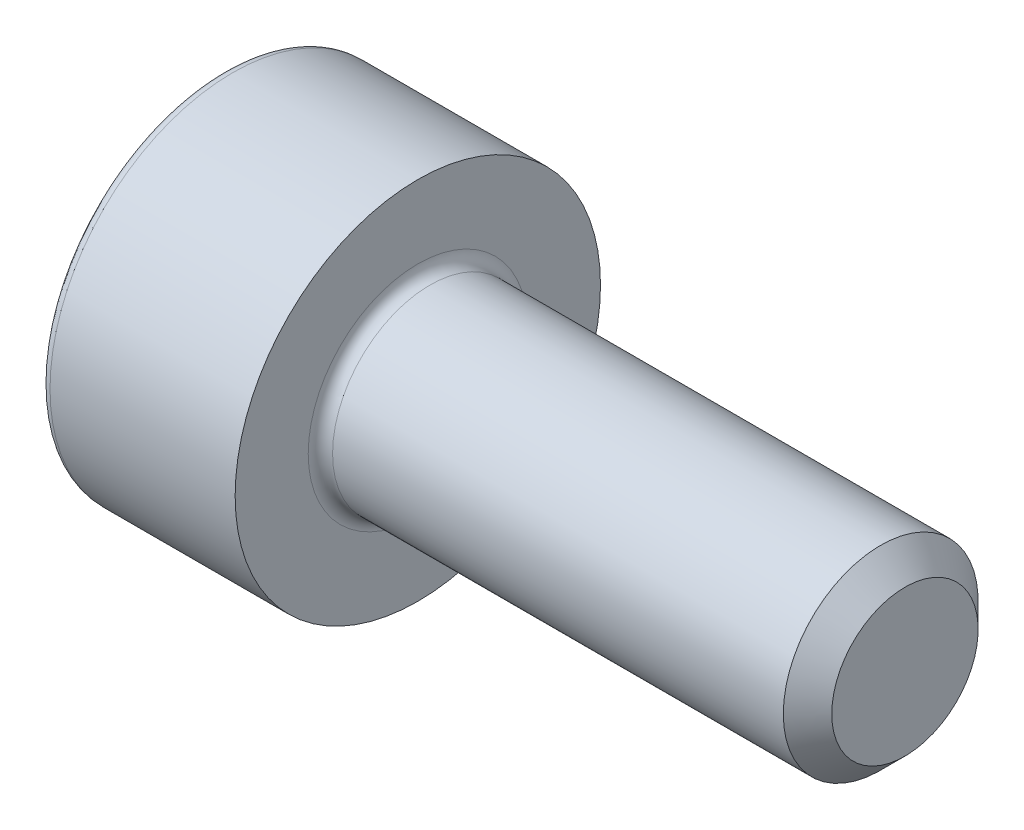
SolidWorks part; units mm, degrees
ref_plane "Front Plane" through (0, 0, 0) normal (0, 0, 1) x (1, 0, 0)
ref_plane "Top Plane" through (0, 0, 0) normal (0, 1, 0) x (1, 0, 0)
ref_plane "Right Plane" through (0, 0, 0) normal (1, 0, 0) x (0, 0, -1)
other "Configuration Table"
sketch "BodySke" plane through (0, 0, 0) normal (0, 0, 1) x (1, 0, 0)
  line L0 (0, 0) -> (5.8492, 0) construction
  line L1 (0, 0) -> (0, 1.5)
  line L2 (0, 1.5) -> (1.6, 1.5)
  line L3 (1.6, 1.5) -> (1.6, 0.8)
  line L4 (1.6, 0.8) -> (5.401, 0.8)
  line L5 (5.401, 0.8) -> (5.6, 0.601)
  line L6 (5.6, 0.601) -> (5.6, 0)
  line L7 (5.6, 0) -> (0, 0)
  line L8 (1.6, 0) -> (1.6, 0.601) construction
  line L9 (1.95, 1.5877) -> (1.95, 0.9267) construction
  dimension "Thread_length" = 4
  dimension "Diameter" = 1.6
  dimension "Thread_minor" = 1.202
  dimension "Body_chamfer_angle" = 45
  dimension "Length" = 4
  dimension "Head_diameter" = 3
  dimension "Head_length" = 1.6
  dimension "Advance" = 0.35
revolve "BaseBody" add sketch "BodySke" angle 360 about L0
cosmetic thread "ThreadCosmetic" [suppressed] parameters "Thread_length"=4, "Thread_minor"=1.202
fillet "Fillet1" radius 0.1 1 edges at (1.6, 0, 0.8)
fillet "Fillet2" radius 0.08 1 edges at (0, 0, 1.5)
sketch "HexSke" plane through (0, 0, 0) normal (1, 0, 0) x (0, 0, -1)
  line L1 (0, 0.866) -> (-0.75, 0.433)
  line L2 (-0.75, 0.433) -> (-0.75, -0.433)
  line L3 (-0.75, -0.433) -> (0, -0.866)
  line L4 (0, -0.866) -> (0.75, -0.433)
  line L5 (0.75, -0.433) -> (0.75, 0.433)
  line L6 (0.75, 0.433) -> (0, 0.866)
  circle A0 centre (0, 0) radius 0.75 construction
  dimension "Hex_size" = 1.5
extrude "Hex" cut sketch "HexSke" along normal blind 0.7
sketch "Hex-PreBroachSke" plane through (0, 0, 0) normal (0, 0, 1) x (1, 0, 0)
  line L0 (0, 0) -> (4.7325, 0) construction
  line L1 (0, 1.42) -> (0, -1.42) construction
  line L2 (0, 0) -> (0, 0.75)
  line L3 (0, 0.75) -> (0.7, 0.75)
  line L4 (0.7, 0.75) -> (1.133, 0)
  line L5 (1.133, 0) -> (0, 0)
  dimension "Hex_depth" = 0.7
  dimension "D1" = 1.5
  dimension "Angle" = 60
revolve "Hex-PreBroach" cut sketch "Hex-PreBroachSke" angle 360 about L0
sketch "ThdSchSke" plane through (0, 0, 0) normal (0, 0, 1) x (1, 0, 0)
  line L0 (0, 0) -> (4.4125, 0) construction
  line L1 (0, 1.42) -> (0, -1.42) construction
  line L2 (5.051, 1.0298) -> (5.051, 0.8)
  line L3 (5.051, 1.0298) -> (5.2808, 1.0298)
  line L4 (5.2808, 1.0298) -> (5.2808, 0.8)
  line L5 (5.2808, 0.8) -> (5.1659, 0.601)
  line L6 (5.1659, 0.601) -> (5.051, 0.8)
  dimension "D1" = 0.35
revolve "ThreadSchematic" [suppressed] cut sketch "ThdSchSke" angle 360 about L0
pattern_linear "ThdSchPat" [suppressed]
equation "\"Thread_length@ThreadCosmetic\" = \"Thread_length@BodySke\""
equation "\"Thread_minor@ThreadCosmetic\" = \"Thread_minor@BodySke\""
equation "\"Hex_depth@Hex-PreBroachSke\" = \"Hex_length@Hex\""
equation "\"D1@Hex-PreBroachSke\" = \"Hex_size@HexSke\""
equation "\"D1@ThdSchSke\" = \"Advance@BodySke\""
equation "\"Advance@ThdSchPat\" = \"Advance@BodySke\""
equation "\"Tooth_Num@ThdSchPat\" =  int( \"Thread_length@BodySke\" / \"Advance@BodySke\" )  - 1"
